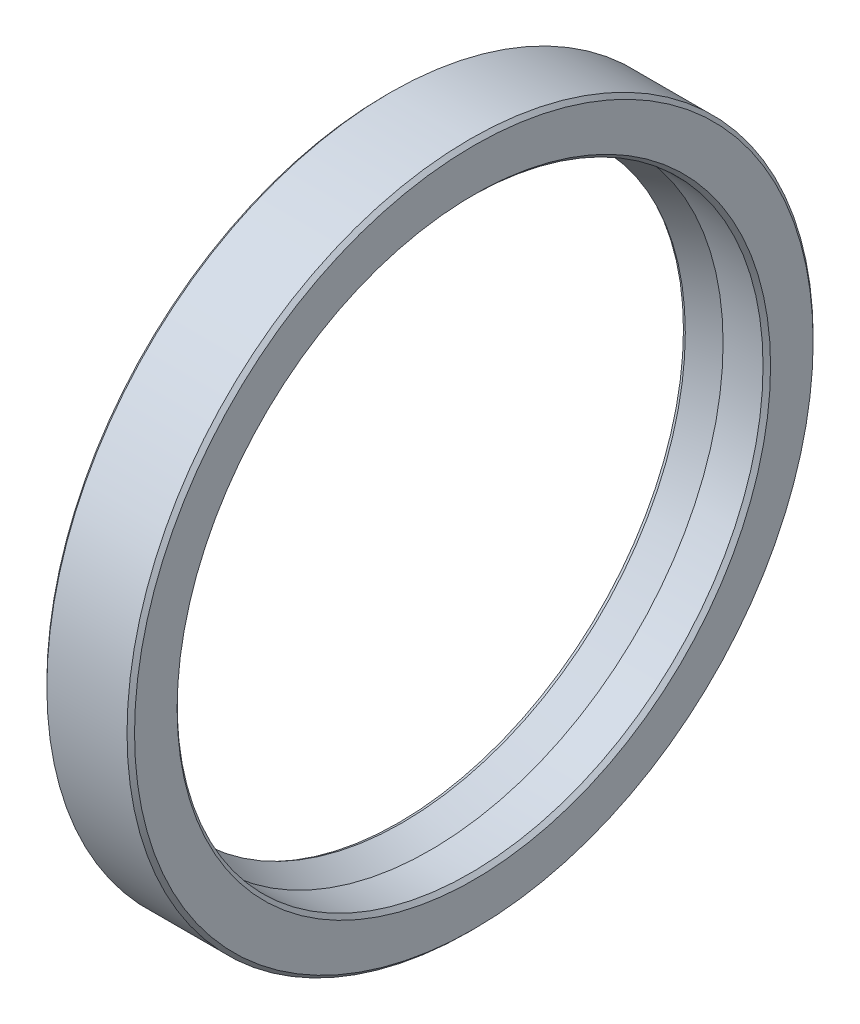
SolidWorks part; units mm, degrees
ref_plane "Front Plane" through (0, 0, 0) normal (0, 0, 1) x (1, 0, 0)
ref_plane "Top Plane" through (0, 0, 0) normal (0, 1, 0) x (1, 0, 0)
ref_plane "Right Plane" through (0, 0, 0) normal (1, 0, 0) x (0, 0, -1)
sketch "Sketch1" plane through (0, 0, 0) normal (0, 0, 1) x (1, 0, 0)
  line L0 (0.3, 0) -> (6.7, 0)
  line L1 (7, -0.3) -> (7, -3.7)
  line L2 (6.7, -4) -> (3.51, -4)
  line L3 (7, -2) -> (-7.3069, -2) construction
  line L4 (0, -0.3) -> (0, -1)
  line L5 (0, -1) -> (4.0465, -1.2514)
  line L6 (3.51, -4) -> (1.2828, -4.7897)
  line L7 (1.3153, -3.8746) -> (4.2771, -2.6969)
  line L8 (1, -4.3393) -> (1, -4.655)
  line L9 (1.2828, -4.7897) -> (1, -4.655)
  line L10 (7, -3.7) -> (6.7, -4)
  line L11 (6.7, 0) -> (7, -0.3)
  line L12 (0, -0.3) -> (0.3, 0)
  line L13 (1.2828, -4.7897) -> (1.2828, -27.3897) construction
  line L14 (1.2828, -27.3897) -> (-8.815, -27.3897) construction
  arc A0 (4.2771, -2.6969) -> (4.0465, -1.2514) centre (4, -2) ccw
  arc A1 (1.3153, -3.8746) -> (1, -4.3393) centre (1.5, -4.3393) ccw
  point P0 (0, 0)
  point P1 (7, 0)
  point P4 (7, -4)
  point P13 (1, -4.89)
  point P16 (1, -4)
  dimension "D9" = 1.5
  dimension "D10" = 0.5
  dimension "D1" = 7
  dimension "D2" = 4
  dimension "D3" = 3.49
  dimension "D4" = 3
  dimension "D5" = 1
  dimension "D6" = 6
  dimension "D7" = 4.89
  dimension "D8" = 4
  dimension "D11" = 0.3
  dimension "D12" = 45
  dimension "D13" = 0.3
  dimension "D14" = 45
  dimension "D15" = 0.3
  dimension "D16" = 45
  dimension "D17" = 0.3
  dimension "D18" = 45
  dimension "D19" = 22.6
revolve "Revolve1" add sketch "Sketch1" angle 360 about L14
ref_plane "Plane1" through (3.5, 0, 0) normal (1, 0, 0) x (0, 0, -1)
